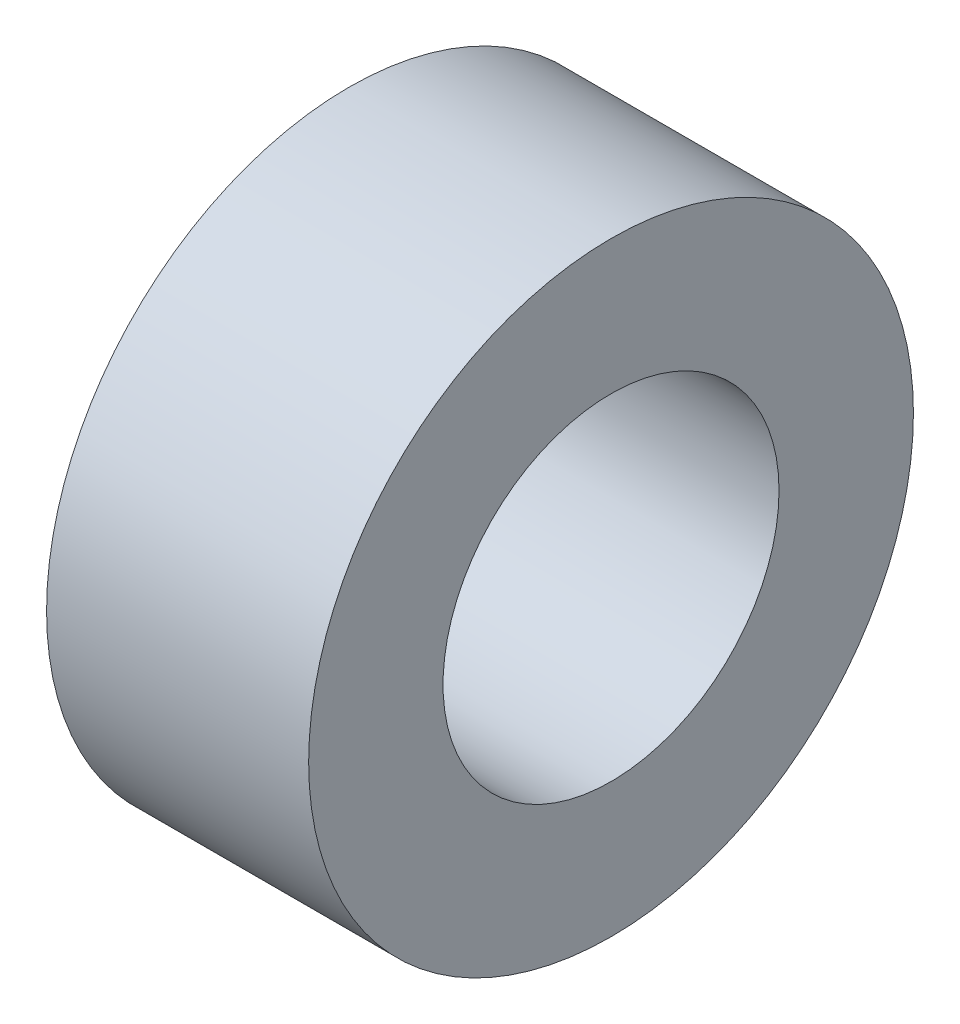
SolidWorks part; units mm, degrees
ref_plane "Front Plane" through (0, 0, 0) normal (0, 0, 1) x (1, 0, 0)
ref_plane "Top Plane" through (0, 0, 0) normal (0, 1, 0) x (1, 0, 0)
ref_plane "Right Plane" through (0, 0, 0) normal (1, 0, 0) x (0, 0, -1)
sketch "Sketch1" plane through (0, 0, 0) normal (0, 0, 1) x (1, 0, 0)
  line L0 (0, -39.0865) -> (0, 35.7212) construction
  line L1 (54.9038, 0) -> (-77.5962, 0) construction
  line L2 (19.5, 45) -> (-19.5, 45)
  line L3 (-19.5, 45) -> (-19.5, 25)
  line L4 (-19.5, 25) -> (19.5, 25)
  line L5 (19.5, 45) -> (19.5, 25)
  point P5 (0, 25)
  point P11 (0, 45)
  dimension "D1" = 20
  dimension "D2" = 39
  dimension "D3" = 90
revolve "Revolve1" add sketch "Sketch1" angle 360 about L1
